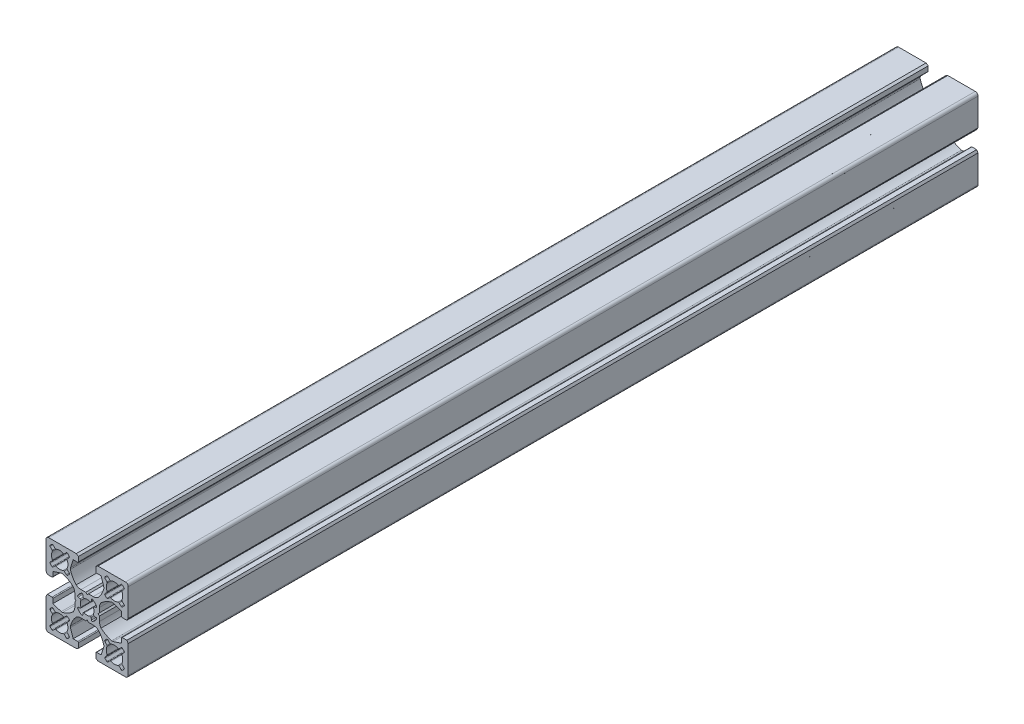
SolidWorks part; units mm, degrees
ref_plane "정면" through (0, 0, 0) normal (0, 0, 1) x (1, 0, 0)
ref_plane "윗면" through (0, 0, 0) normal (0, 1, 0) x (1, 0, 0)
ref_plane "우측면" through (0, 0, 0) normal (1, 0, 0) x (0, 0, -1)
sketch "Model" plane through (0, 0, 0) normal (0, 0, 1) x (1, 0, 0)
  line L0 (465.6218, 205.5838) -> (465.6218, 209.9838) construction
  line L1 (463.4218, 207.7838) -> (467.8218, 207.7838) construction
  line L2 (462.8793, 206.102) -> (462.1388, 205.3614)
  line L3 (463.1994, 204.3007) -> (463.94, 205.0413)
  line L4 (467.3037, 205.0413) -> (468.0443, 204.3007)
  line L5 (469.1049, 205.3614) -> (468.3643, 206.102)
  line L6 (468.3643, 209.4657) -> (469.1049, 210.2063)
  line L7 (468.0443, 211.2669) -> (467.3037, 210.5263)
  line L8 (463.94, 210.5263) -> (463.1994, 211.2669)
  line L9 (462.1388, 210.2063) -> (462.8793, 209.4657)
  line L10 (463.4211, 187.7832) -> (467.8211, 187.7829) construction
  line L11 (465.6212, 189.9831) -> (465.6209, 185.5831) construction
  line L12 (462.8787, 189.4651) -> (462.1382, 190.2057)
  line L13 (463.1989, 191.2663) -> (463.9394, 190.5257)
  line L14 (467.3031, 190.5254) -> (468.0438, 191.2659)
  line L15 (469.1043, 190.2052) -> (468.3637, 189.4647)
  line L16 (468.3634, 186.101) -> (469.1039, 185.3604)
  line L17 (468.0432, 184.2998) -> (467.3027, 185.0404)
  line L18 (463.939, 185.0407) -> (463.1984, 184.3002)
  line L19 (462.1378, 185.3609) -> (462.8784, 186.1014)
  line L20 (448.3673, 189.4651) -> (449.1078, 190.2057)
  line L21 (448.0471, 191.2663) -> (447.3066, 190.5257)
  line L22 (443.9429, 190.5254) -> (443.2023, 191.2659)
  line L23 (442.1417, 190.2052) -> (442.8823, 189.4647)
  line L24 (442.8826, 186.101) -> (442.1421, 185.3604)
  line L25 (443.2028, 184.2998) -> (443.9433, 185.0404)
  line L26 (447.307, 185.0407) -> (448.0476, 184.3002)
  line L27 (449.1082, 185.3609) -> (448.3676, 186.1014)
  line L28 (445.6248, 189.9831) -> (445.6251, 185.5831) construction
  line L29 (447.825, 187.7832) -> (443.425, 187.7829) construction
  line L30 (447.8242, 207.7838) -> (443.4242, 207.7838) construction
  line L31 (445.6242, 205.5838) -> (445.6242, 209.9838) construction
  line L32 (471.0819, 197.7838) -> (439.4, 197.7838) construction
  line L33 (455.6242, 181.8427) -> (455.6242, 213.7801) construction
  line L34 (457.2103, 201.0212) -> (457.0767, 200.2802)
  line L35 (454.1716, 200.2802) -> (454.0381, 201.0212)
  line L36 (452.3868, 199.37) -> (453.1278, 199.2364)
  line L37 (453.1278, 196.3313) -> (452.3868, 196.1977)
  line L38 (454.0381, 194.5465) -> (454.1716, 195.2874)
  line L39 (457.0767, 195.2874) -> (457.2103, 194.5465)
  line L40 (458.8615, 196.1977) -> (458.1206, 196.3313)
  line L41 (458.1206, 199.2364) -> (458.8615, 199.37)
  line L42 (448.3667, 206.102) -> (449.1073, 205.3614)
  line L43 (448.0466, 204.3007) -> (447.306, 205.0413)
  line L44 (443.9423, 205.0413) -> (443.2018, 204.3007)
  line L45 (442.1411, 205.3614) -> (442.8817, 206.102)
  line L46 (442.8817, 209.4657) -> (442.1411, 210.2063)
  line L47 (443.2018, 211.2669) -> (443.9423, 210.5263)
  line L48 (447.306, 210.5263) -> (448.0466, 211.2669)
  line L49 (449.1073, 210.2063) -> (448.3667, 209.4657)
  line L50 (459.5742, 182.7838) -> (458.7742, 183.2838)
  line L51 (458.7742, 183.2838) -> (458.7742, 184.9838)
  line L52 (459.0742, 185.2838) -> (460.7242, 185.2838)
  line L53 (460.7242, 185.2838) -> (461.7118, 188.3356)
  line L54 (457.842, 193.2838) -> (456.1242, 193.2838)
  line L55 (456.1242, 193.2838) -> (455.6242, 193.7838)
  line L56 (455.6242, 193.7838) -> (455.1242, 193.2838)
  line L57 (455.1242, 193.2838) -> (453.4063, 193.2838)
  line L58 (449.5366, 188.3356) -> (450.5242, 185.2838)
  line L59 (450.5242, 185.2838) -> (452.1742, 185.2838)
  line L60 (452.4742, 184.9838) -> (452.4742, 183.2838)
  line L61 (452.4742, 183.2838) -> (451.6742, 182.7838)
  line L62 (451.6742, 182.7838) -> (441.6242, 182.7838)
  line L63 (440.6242, 183.7838) -> (440.6242, 193.8338)
  line L64 (440.6242, 193.8338) -> (441.1242, 194.6338)
  line L65 (441.1242, 194.6338) -> (442.8242, 194.6338)
  line L66 (443.1242, 194.3338) -> (443.1242, 192.6838)
  line L67 (443.1242, 192.6838) -> (446.1759, 191.6962)
  line L68 (451.1242, 195.566) -> (451.1242, 197.2838)
  line L69 (451.1242, 197.2838) -> (451.6242, 197.7838)
  line L70 (451.6242, 197.7838) -> (451.1242, 198.2838)
  line L71 (451.1242, 198.2838) -> (451.1242, 200.0017)
  line L72 (446.1759, 203.8714) -> (443.1242, 202.8838)
  line L73 (443.1242, 202.8838) -> (443.1242, 201.2338)
  line L74 (442.8242, 200.9338) -> (441.1242, 200.9338)
  line L75 (441.1242, 200.9338) -> (440.6242, 201.7338)
  line L76 (440.6242, 201.7338) -> (440.6242, 211.7838)
  line L77 (441.6242, 212.7838) -> (451.6742, 212.7838)
  line L78 (451.6742, 212.7838) -> (452.4742, 212.2838)
  line L79 (452.4742, 212.2838) -> (452.4742, 210.5838)
  line L80 (452.1742, 210.2838) -> (450.5242, 210.2838)
  line L81 (450.5242, 210.2838) -> (449.5366, 207.2321)
  line L82 (453.4063, 202.2838) -> (455.1242, 202.2838)
  line L83 (455.1242, 202.2838) -> (455.6242, 201.7838)
  line L84 (455.6242, 201.7838) -> (456.1242, 202.2838)
  line L85 (456.1242, 202.2838) -> (457.842, 202.2838)
  line L86 (461.7118, 207.2321) -> (460.7242, 210.2838)
  line L87 (460.7242, 210.2838) -> (459.0742, 210.2838)
  line L88 (458.7742, 210.5838) -> (458.7742, 212.2838)
  line L89 (458.7742, 212.2838) -> (459.5742, 212.7838)
  line L90 (459.5742, 212.7838) -> (469.6242, 212.7838)
  line L91 (470.6242, 211.7838) -> (470.6242, 201.7338)
  line L92 (470.6242, 201.7338) -> (470.1242, 200.9338)
  line L93 (470.1242, 200.9338) -> (468.4242, 200.9338)
  line L94 (468.1242, 201.2338) -> (468.1242, 202.8838)
  line L95 (468.1242, 202.8838) -> (465.0724, 203.8714)
  line L96 (460.1242, 200.0017) -> (460.1242, 198.2838)
  line L97 (460.1242, 198.2838) -> (459.6242, 197.7838)
  line L98 (459.6242, 197.7838) -> (460.1242, 197.2838)
  line L99 (460.1242, 197.2838) -> (460.1242, 195.566)
  line L100 (465.0724, 191.6962) -> (468.1242, 192.6838)
  line L101 (468.1242, 192.6838) -> (468.1242, 194.3338)
  line L102 (468.4242, 194.6338) -> (470.1242, 194.6338)
  line L103 (470.1242, 194.6338) -> (470.6242, 193.8338)
  line L104 (470.6242, 193.8338) -> (470.6242, 183.7838)
  line L105 (469.6242, 182.7838) -> (459.5742, 182.7838)
  arc A0 (462.8793, 206.102) -> (462.9358, 206.4477) centre (462.6672, 206.3141) ccw
  arc A1 (462.1388, 205.3614) -> (462.1172, 204.9611) centre (462.3509, 205.1493) ccw
  arc A2 (462.1172, 204.9611) -> (462.7991, 204.2792) centre (465.6218, 207.7838) ccw
  arc A3 (462.7991, 204.2792) -> (463.1994, 204.3007) centre (462.9873, 204.5129) ccw
  arc A4 (464.2857, 205.0978) -> (463.94, 205.0413) centre (464.1521, 204.8292) ccw
  arc A5 (464.2857, 205.0978) -> (466.9579, 205.0978) centre (465.6218, 207.7838) ccw
  arc A6 (467.3037, 205.0413) -> (466.9579, 205.0978) centre (467.0916, 204.8292) ccw
  arc A7 (468.0443, 204.3007) -> (468.4446, 204.2792) centre (468.2564, 204.5129) ccw
  arc A8 (468.4446, 204.2792) -> (469.1264, 204.9611) centre (465.6218, 207.7838) ccw
  arc A9 (469.1264, 204.9611) -> (469.1049, 205.3614) centre (468.8928, 205.1493) ccw
  arc A10 (468.3079, 206.4477) -> (468.3643, 206.102) centre (468.5765, 206.3141) ccw
  arc A11 (468.3079, 206.4477) -> (468.3079, 209.1199) centre (465.6218, 207.7838) ccw
  arc A12 (468.3643, 209.4657) -> (468.3079, 209.1199) centre (468.5765, 209.2536) ccw
  arc A13 (469.1049, 210.2063) -> (469.1264, 210.6066) centre (468.8928, 210.4184) ccw
  arc A14 (469.1264, 210.6066) -> (468.4446, 211.2884) centre (465.6218, 207.7838) ccw
  arc A15 (468.4446, 211.2884) -> (468.0443, 211.2669) centre (468.2564, 211.0548) ccw
  arc A16 (466.9579, 210.4699) -> (467.3037, 210.5263) centre (467.0916, 210.7385) ccw
  arc A17 (466.9579, 210.4699) -> (464.2857, 210.4699) centre (465.6218, 207.7838) ccw
  arc A18 (463.94, 210.5263) -> (464.2857, 210.4699) centre (464.1521, 210.7385) ccw
  arc A19 (463.1994, 211.2669) -> (462.7991, 211.2884) centre (462.9873, 211.0548) ccw
  arc A20 (462.7991, 211.2884) -> (462.1172, 210.6066) centre (465.6218, 207.7838) ccw
  arc A21 (462.1172, 210.6066) -> (462.1388, 210.2063) centre (462.3509, 210.4184) ccw
  arc A22 (462.9358, 209.1199) -> (462.8793, 209.4657) centre (462.6672, 209.2536) ccw
  arc A23 (462.9358, 209.1199) -> (462.9358, 206.4477) centre (465.6218, 207.7838) ccw
  arc A24 (462.9351, 189.1194) -> (462.8787, 189.4651) centre (462.6665, 189.253) ccw
  arc A25 (462.1167, 190.6061) -> (462.1382, 190.2057) centre (462.3503, 190.4179) ccw
  arc A26 (462.7986, 191.2879) -> (462.1167, 190.6061) centre (465.6211, 187.7831) ccw
  arc A27 (463.1989, 191.2663) -> (462.7986, 191.2879) centre (462.9868, 191.0542) ccw
  arc A28 (463.9394, 190.5257) -> (464.2852, 190.4692) centre (464.1516, 190.7378) ccw
  arc A29 (466.9574, 190.469) -> (464.2852, 190.4692) centre (465.6211, 187.7831) ccw
  arc A30 (466.9574, 190.469) -> (467.3031, 190.5254) centre (467.091, 190.7376) ccw
  arc A31 (468.4441, 191.2874) -> (468.0438, 191.2659) centre (468.2559, 191.0538) ccw
  arc A32 (469.1259, 190.6055) -> (468.4441, 191.2874) centre (465.6211, 187.7831) ccw
  arc A33 (469.1043, 190.2052) -> (469.1259, 190.6055) centre (468.8922, 190.4174) ccw
  arc A34 (468.3637, 189.4647) -> (468.3072, 189.119) centre (468.5758, 189.2525) ccw
  arc A35 (468.307, 186.4467) -> (468.3072, 189.119) centre (465.6211, 187.7831) ccw
  arc A36 (468.307, 186.4467) -> (468.3634, 186.101) centre (468.5756, 186.3131) ccw
  arc A37 (469.1254, 184.96) -> (469.1039, 185.3604) centre (468.8918, 185.1482) ccw
  arc A38 (468.4435, 184.2782) -> (469.1254, 184.96) centre (465.6211, 187.7831) ccw
  arc A39 (468.0432, 184.2998) -> (468.4435, 184.2782) centre (468.2554, 184.5119) ccw
  arc A40 (467.3027, 185.0404) -> (466.957, 185.0969) centre (467.0905, 184.8283) ccw
  arc A41 (464.2847, 185.0971) -> (466.957, 185.0969) centre (465.6211, 187.7831) ccw
  arc A42 (464.2847, 185.0971) -> (463.939, 185.0407) centre (464.1511, 184.8285) ccw
  arc A43 (462.798, 184.2787) -> (463.1984, 184.3002) centre (462.9862, 184.5123) ccw
  arc A44 (462.1162, 184.9606) -> (462.798, 184.2787) centre (465.6211, 187.7831) ccw
  arc A45 (462.1378, 185.3609) -> (462.1162, 184.9606) centre (462.3499, 185.1488) ccw
  arc A46 (462.8784, 186.1014) -> (462.9349, 186.4472) centre (462.6663, 186.3136) ccw
  arc A47 (462.9351, 189.1194) -> (462.9349, 186.4472) centre (465.6211, 187.7831) ccw
  arc A48 (448.3673, 189.4651) -> (448.3109, 189.1194) centre (448.5795, 189.253) ccw
  arc A49 (449.1078, 190.2057) -> (449.1293, 190.6061) centre (448.8957, 190.4179) ccw
  arc A50 (449.1293, 190.6061) -> (448.4474, 191.2879) centre (445.625, 187.7831) ccw
  arc A51 (448.4474, 191.2879) -> (448.0471, 191.2663) centre (448.2593, 191.0542) ccw
  arc A52 (446.9609, 190.4692) -> (447.3066, 190.5257) centre (447.0944, 190.7378) ccw
  arc A53 (446.9609, 190.4692) -> (444.2886, 190.469) centre (445.625, 187.7831) ccw
  arc A54 (443.9429, 190.5254) -> (444.2886, 190.469) centre (444.155, 190.7376) ccw
  arc A55 (443.2023, 191.2659) -> (442.8019, 191.2874) centre (442.9901, 191.0538) ccw
  arc A56 (442.8019, 191.2874) -> (442.1201, 190.6055) centre (445.625, 187.7831) ccw
  arc A57 (442.1201, 190.6055) -> (442.1417, 190.2052) centre (442.3538, 190.4174) ccw
  arc A58 (442.9388, 189.119) -> (442.8823, 189.4647) centre (442.6702, 189.2525) ccw
  arc A59 (442.9388, 189.119) -> (442.939, 186.4467) centre (445.625, 187.7831) ccw
  arc A60 (442.8826, 186.101) -> (442.939, 186.4467) centre (442.6704, 186.3131) ccw
  arc A61 (442.1421, 185.3604) -> (442.1206, 184.96) centre (442.3542, 185.1482) ccw
  arc A62 (442.1206, 184.96) -> (442.8025, 184.2782) centre (445.625, 187.7831) ccw
  arc A63 (442.8025, 184.2782) -> (443.2028, 184.2998) centre (442.9907, 184.5119) ccw
  arc A64 (444.2891, 185.0969) -> (443.9433, 185.0404) centre (444.1555, 184.8283) ccw
  arc A65 (444.2891, 185.0969) -> (446.9613, 185.0971) centre (445.625, 187.7831) ccw
  arc A66 (447.307, 185.0407) -> (446.9613, 185.0971) centre (447.0949, 184.8285) ccw
  arc A67 (448.0476, 184.3002) -> (448.448, 184.2787) centre (448.2598, 184.5123) ccw
  arc A68 (448.448, 184.2787) -> (449.1298, 184.9606) centre (445.625, 187.7831) ccw
  arc A69 (449.1298, 184.9606) -> (449.1082, 185.3609) centre (448.8961, 185.1488) ccw
  arc A70 (448.3111, 186.4472) -> (448.3676, 186.1014) centre (448.5797, 186.3136) ccw
  arc A71 (448.3111, 186.4472) -> (448.3109, 189.1194) centre (445.625, 187.7831) ccw
  arc A72 (458.8615, 199.37) -> (459.0666, 199.8178) centre (458.8083, 199.6652) ccw
  arc A73 (459.0666, 199.8178) -> (457.6582, 201.2262) centre (455.623, 197.7827) ccw
  arc A74 (457.6582, 201.2262) -> (457.2103, 201.0212) centre (457.5055, 200.9679) ccw
  arc A75 (456.6575, 200.0603) -> (457.0767, 200.2802) centre (456.7815, 200.3335) ccw
  arc A76 (456.6575, 200.0603) -> (454.5909, 200.0603) centre (455.6242, 197.7838) ccw
  arc A77 (454.1716, 200.2802) -> (454.5909, 200.0603) centre (454.4669, 200.3335) ccw
  arc A78 (454.0381, 201.0212) -> (453.5902, 201.2262) centre (453.7428, 200.9679) ccw
  arc A79 (453.5902, 201.2262) -> (452.1818, 199.8178) centre (455.6253, 197.7827) ccw
  arc A80 (452.1818, 199.8178) -> (452.3868, 199.37) centre (452.4401, 199.6652) ccw
  arc A81 (453.3477, 198.8171) -> (453.1278, 199.2364) centre (453.0745, 198.9411) ccw
  arc A82 (453.3477, 198.8171) -> (453.3477, 196.7505) centre (455.6242, 197.7838) ccw
  arc A83 (453.1278, 196.3313) -> (453.3477, 196.7505) centre (453.0745, 196.6265) ccw
  arc A84 (452.3868, 196.1977) -> (452.1818, 195.7498) centre (452.4401, 195.9025) ccw
  arc A85 (452.1818, 195.7498) -> (453.5902, 194.3414) centre (455.6253, 197.785) ccw
  arc A86 (453.5902, 194.3414) -> (454.0381, 194.5465) centre (453.7428, 194.5997) ccw
  arc A87 (454.5909, 195.5074) -> (454.1716, 195.2874) centre (454.4669, 195.2342) ccw
  arc A88 (454.5909, 195.5074) -> (456.6575, 195.5074) centre (455.6242, 197.7838) ccw
  arc A89 (457.0767, 195.2874) -> (456.6575, 195.5074) centre (456.7815, 195.2342) ccw
  arc A90 (457.2103, 194.5465) -> (457.6582, 194.3414) centre (457.5055, 194.5997) ccw
  arc A91 (457.6582, 194.3414) -> (459.0666, 195.7498) centre (455.623, 197.785) ccw
  arc A92 (459.0666, 195.7498) -> (458.8615, 196.1977) centre (458.8083, 195.9025) ccw
  arc A93 (457.9006, 196.7505) -> (458.1206, 196.3313) centre (458.1738, 196.6265) ccw
  arc A94 (457.9006, 196.7505) -> (457.9006, 198.8171) centre (455.6242, 197.7838) ccw
  arc A95 (458.1206, 199.2364) -> (457.9006, 198.8171) centre (458.1738, 198.9411) ccw
  arc A96 (448.3102, 206.4477) -> (448.3667, 206.102) centre (448.5788, 206.3141) ccw
  arc A97 (449.1288, 204.9611) -> (449.1073, 205.3614) centre (448.8951, 205.1493) ccw
  arc A98 (448.4469, 204.2792) -> (449.1288, 204.9611) centre (445.6242, 207.7838) ccw
  arc A99 (448.0466, 204.3007) -> (448.4469, 204.2792) centre (448.2587, 204.5129) ccw
  arc A100 (447.306, 205.0413) -> (446.9603, 205.0978) centre (447.0939, 204.8292) ccw
  arc A101 (444.2881, 205.0978) -> (446.9603, 205.0978) centre (445.6242, 207.7838) ccw
  arc A102 (444.2881, 205.0978) -> (443.9423, 205.0413) centre (444.1545, 204.8292) ccw
  arc A103 (442.8014, 204.2792) -> (443.2018, 204.3007) centre (442.9896, 204.5129) ccw
  arc A104 (442.1196, 204.9611) -> (442.8014, 204.2792) centre (445.6242, 207.7838) ccw
  arc A105 (442.1411, 205.3614) -> (442.1196, 204.9611) centre (442.3532, 205.1493) ccw
  arc A106 (442.8817, 206.102) -> (442.9381, 206.4477) centre (442.6695, 206.3141) ccw
  arc A107 (442.9381, 209.1199) -> (442.9381, 206.4477) centre (445.6242, 207.7838) ccw
  arc A108 (442.9381, 209.1199) -> (442.8817, 209.4657) centre (442.6695, 209.2536) ccw
  arc A109 (442.1196, 210.6066) -> (442.1411, 210.2063) centre (442.3532, 210.4184) ccw
  arc A110 (442.8014, 211.2884) -> (442.1196, 210.6066) centre (445.6242, 207.7838) ccw
  arc A111 (443.2018, 211.2669) -> (442.8014, 211.2884) centre (442.9896, 211.0548) ccw
  arc A112 (443.9423, 210.5263) -> (444.2881, 210.4699) centre (444.1545, 210.7385) ccw
  arc A113 (446.9603, 210.4699) -> (444.2881, 210.4699) centre (445.6242, 207.7838) ccw
  arc A114 (446.9603, 210.4699) -> (447.306, 210.5263) centre (447.0939, 210.7385) ccw
  arc A115 (448.4469, 211.2884) -> (448.0466, 211.2669) centre (448.2587, 211.0548) ccw
  arc A116 (449.1288, 210.6066) -> (448.4469, 211.2884) centre (445.6242, 207.7838) ccw
  arc A117 (449.1073, 210.2063) -> (449.1288, 210.6066) centre (448.8951, 210.4184) ccw
  arc A118 (448.3667, 209.4657) -> (448.3102, 209.1199) centre (448.5788, 209.2536) ccw
  arc A119 (448.3102, 206.4477) -> (448.3102, 209.1199) centre (445.6242, 207.7838) ccw
  arc A120 (459.0742, 185.2838) -> (458.7742, 184.9838) centre (459.0742, 184.9838) ccw
  arc A121 (461.7118, 188.3356) -> (461.7375, 188.856) centre (460.7604, 188.6435) ccw
  arc A122 (461.7375, 188.856) -> (459.6282, 192.6941) centre (452.2648, 186.1487) ccw
  arc A123 (459.6282, 192.6941) -> (457.842, 193.2838) centre (457.842, 190.2838) ccw
  arc A124 (453.4063, 193.2838) -> (451.6202, 192.6941) centre (453.4063, 190.2838) ccw
  arc A125 (451.6202, 192.6941) -> (449.5108, 188.856) centre (458.9836, 186.1487) ccw
  arc A126 (449.5108, 188.856) -> (449.5366, 188.3356) centre (450.488, 188.6435) ccw
  arc A127 (452.4742, 184.9838) -> (452.1742, 185.2838) centre (452.1742, 184.9838) ccw
  arc A128 (440.6242, 183.7838) -> (441.6242, 182.7838) centre (441.6242, 183.7838) ccw
  arc A129 (443.1242, 194.3338) -> (442.8242, 194.6338) centre (442.8242, 194.3338) ccw
  arc A130 (446.1759, 191.6962) -> (446.6963, 191.6705) centre (446.4838, 192.6476) ccw
  arc A131 (446.6963, 191.6705) -> (450.5345, 193.7798) centre (443.9891, 201.1432) ccw
  arc A132 (450.5345, 193.7798) -> (451.1242, 195.566) centre (448.1242, 195.566) ccw
  arc A133 (451.1242, 200.0017) -> (450.5345, 201.7878) centre (448.1242, 200.0017) ccw
  arc A134 (450.5345, 201.7878) -> (446.6963, 203.8972) centre (443.9891, 194.4244) ccw
  arc A135 (446.6963, 203.8972) -> (446.1759, 203.8714) centre (446.4838, 202.92) ccw
  arc A136 (442.8242, 200.9338) -> (443.1242, 201.2338) centre (442.8242, 201.2338) ccw
  arc A137 (441.6242, 212.7838) -> (440.6242, 211.7838) centre (441.6242, 211.7838) ccw
  arc A138 (452.1742, 210.2838) -> (452.4742, 210.5838) centre (452.1742, 210.5838) ccw
  arc A139 (449.5366, 207.2321) -> (449.5108, 206.7117) centre (450.488, 206.9242) ccw
  arc A140 (449.5108, 206.7117) -> (451.6202, 202.8735) centre (458.9836, 209.4189) ccw
  arc A141 (451.6202, 202.8735) -> (453.4063, 202.2838) centre (453.4063, 205.2838) ccw
  arc A142 (457.842, 202.2838) -> (459.6282, 202.8735) centre (457.842, 205.2838) ccw
  arc A143 (459.6282, 202.8735) -> (461.7375, 206.7117) centre (452.2648, 209.4189) ccw
  arc A144 (461.7375, 206.7117) -> (461.7118, 207.2321) centre (460.7604, 206.9242) ccw
  arc A145 (458.7742, 210.5838) -> (459.0742, 210.2838) centre (459.0742, 210.5838) ccw
  arc A146 (470.6242, 211.7838) -> (469.6242, 212.7838) centre (469.6242, 211.7838) ccw
  arc A147 (468.1242, 201.2338) -> (468.4242, 200.9338) centre (468.4242, 201.2338) ccw
  arc A148 (465.0724, 203.8714) -> (464.552, 203.8972) centre (464.7645, 202.92) ccw
  arc A149 (464.552, 203.8972) -> (460.7139, 201.7878) centre (467.2593, 194.4244) ccw
  arc A150 (460.7139, 201.7878) -> (460.1242, 200.0017) centre (463.1242, 200.0017) ccw
  arc A151 (460.1242, 195.566) -> (460.7139, 193.7798) centre (463.1242, 195.566) ccw
  arc A152 (460.7139, 193.7798) -> (464.552, 191.6705) centre (467.2593, 201.1432) ccw
  arc A153 (464.552, 191.6705) -> (465.0724, 191.6962) centre (464.7645, 192.6476) ccw
  arc A154 (468.4242, 194.6338) -> (468.1242, 194.3338) centre (468.4242, 194.3338) ccw
  arc A155 (469.6242, 182.7838) -> (470.6242, 183.7838) centre (469.6242, 183.7838) ccw
  dimension "D1" = 30
  dimension "D2" = 30
  dimension "D3" = 15
  dimension "D4" = 15
extrude "보스-돌출1" add sketch "Model" along normal blind 310
